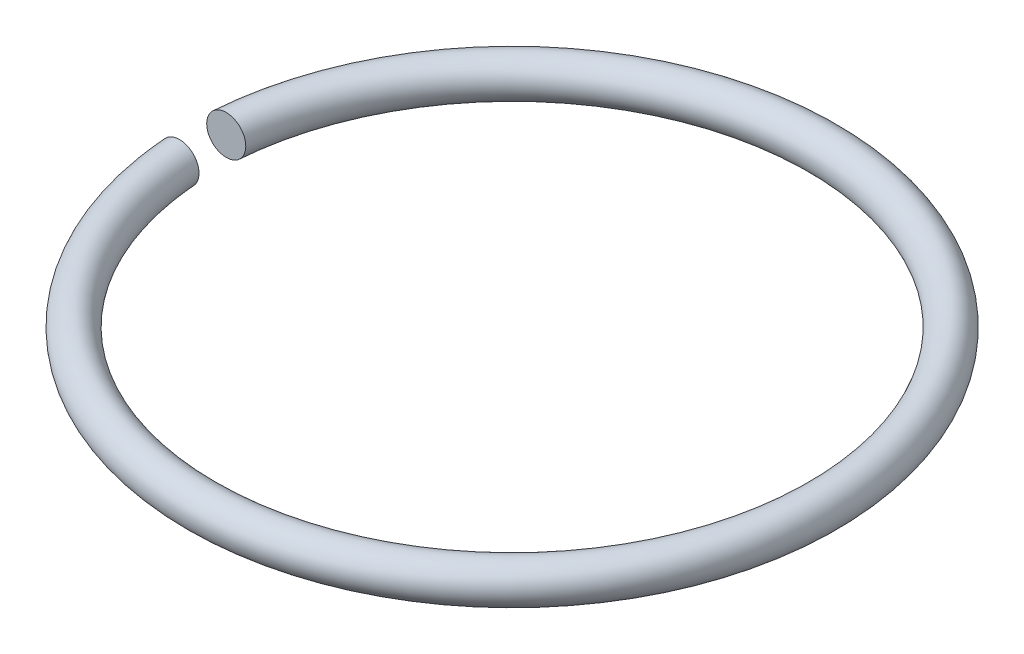
SolidWorks part; units mm, degrees
ref_plane "Спереди" through (0, 0, 0) normal (0, 0, 1) x (1, 0, 0)
ref_plane "Сверху" through (0, 0, 0) normal (0, 1, 0) x (1, 0, 0)
ref_plane "Справа" through (0, 0, 0) normal (1, 0, 0) x (0, 0, -1)
sketch "Эскиз1" plane through (0, 0, 0) normal (0, 0, 1) x (1, 0, 0)
  line L0 (0, 0) -> (0, 42.813) construction
  circle A0 centre (-19.9, 1.25) radius 1.25
  dimension "D1" = 2.5
  dimension "D2" = 19.9
  dimension "D3" = 1.25
revolve "Повернуть1" add sketch "Эскиз1" angle 360 about L0
sketch "Эскиз2" plane through (0, 0, 0) normal (0, 1, 0) x (1, 0, 0)
  line L0 (0, 0) -> (-29.3009, 0) construction
  line L1 (-24.8398, 1.5) -> (-16.0773, 1.5)
  line L2 (-24.8398, 1.5) -> (-24.8398, -1.5)
  line L3 (-24.8398, -1.5) -> (-16.0773, -1.5)
  line L4 (-16.0773, 1.5) -> (-16.0773, -1.5)
  dimension "D1" = 3
  dimension "D2" = 1.5
extrude "Вырез-Вытянуть1" cut sketch "Эскиз2" along normal through all
